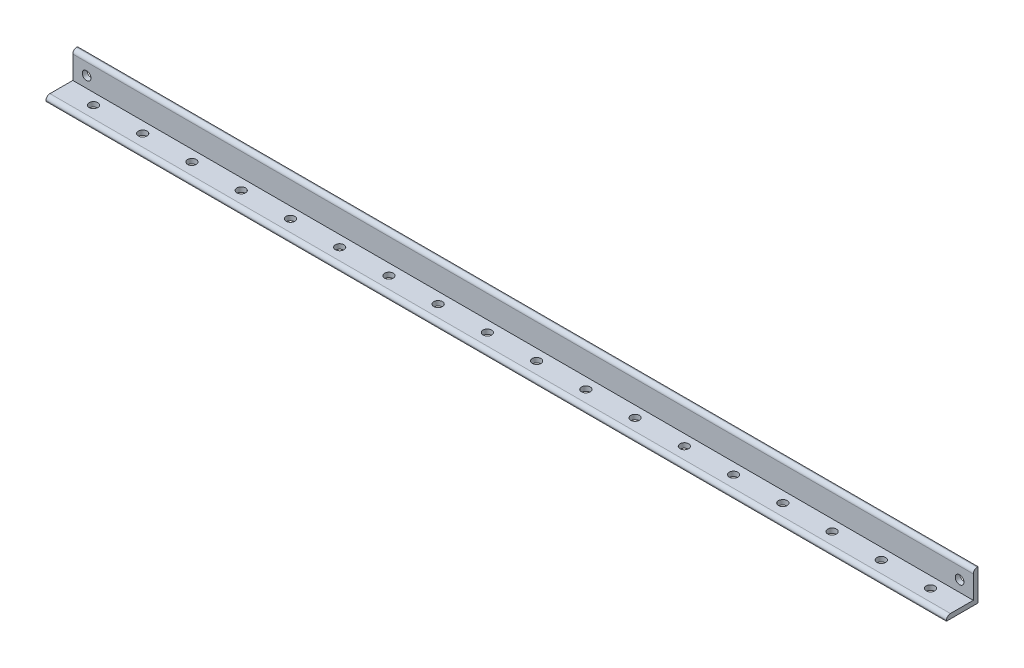
SolidWorks part; units mm, degrees
ref_plane "前视基准面" through (0, 0, 0) normal (0, 0, 1) x (1, 0, 0)
ref_plane "上视基准面" through (0, 0, 0) normal (0, 1, 0) x (1, 0, 0)
ref_plane "右视基准面" through (0, 0, 0) normal (1, 0, 0) x (0, 0, -1)
sketch "草图1" plane through (0, 0, 0) normal (0, 0, 1) x (1, 0, 0)
  line L1 (0, 0) -> (2286, 0)
  line L2 (0, 0) -> (0, 80)
  line L3 (0, 80) -> (2286, 80)
  line L4 (2286, 0) -> (2286, 80)
  dimension "D1" = 2286
  dimension "D2" = 80
extrude "拉伸1" add sketch "草图1" along normal blind 80
sketch "草图3" plane through (0, 0, 0) normal (-1, 0, 0) x (0, 0, 1)
  line L0 (80, 80) -> (80, 0) construction
  line L1 (12, 80) -> (80, 80)
  line L2 (12, 80) -> (12, 12)
  line L3 (12, 12) -> (80, 12)
  line L4 (80, 80) -> (80, 12)
  line L5 (80, 80) -> (0, 80) construction
  line L6 (80, 0) -> (0, 0) construction
  line L7 (0, 80) -> (0, 0) construction
  dimension "D1" = 12
  dimension "D2" = 12
extrude "拉伸2" cut sketch "草图3" against normal through all
fillet "圆角1" radius 10 2 edges at (1143, 12, 80) (1143, 80, 12)
sketch "草图4" plane through (0, 0, 0) normal (0, 0, -1) x (-1, 0, 0)
  line L0 (-2286, 0) -> (-2286, 80) construction
  line L1 (0, 0) -> (-2286, 0) construction
  circle A0 centre (-2251.25, 40) radius 11
  dimension "D1" = 34.75
  dimension "D3" = 22
  dimension "D2" = 40
extrude "拉伸3" cut sketch "草图4" against normal through all
pattern_linear "阵列(线性)1" count 2 spacing 2216.1769 along (-1, 0, 0) of "拉伸3"
sketch "草图5" plane through (0, 0, 0) normal (0, -1, 0) x (1, 0, 0)
  line L0 (0, 80) -> (0, 0) construction
  line L1 (0, 0) -> (2286, 0) construction
  circle A0 centre (80.5, 40) radius 11
  point P2 (0, 40)
  dimension "D1" = 80.5
  dimension "D3" = 22
  dimension "D2" = 40
extrude "拉伸4" cut sketch "草图5" against normal through all
pattern_linear "阵列(线性)2" count 18 spacing 125 along (1, 0, 0) of "拉伸4"
